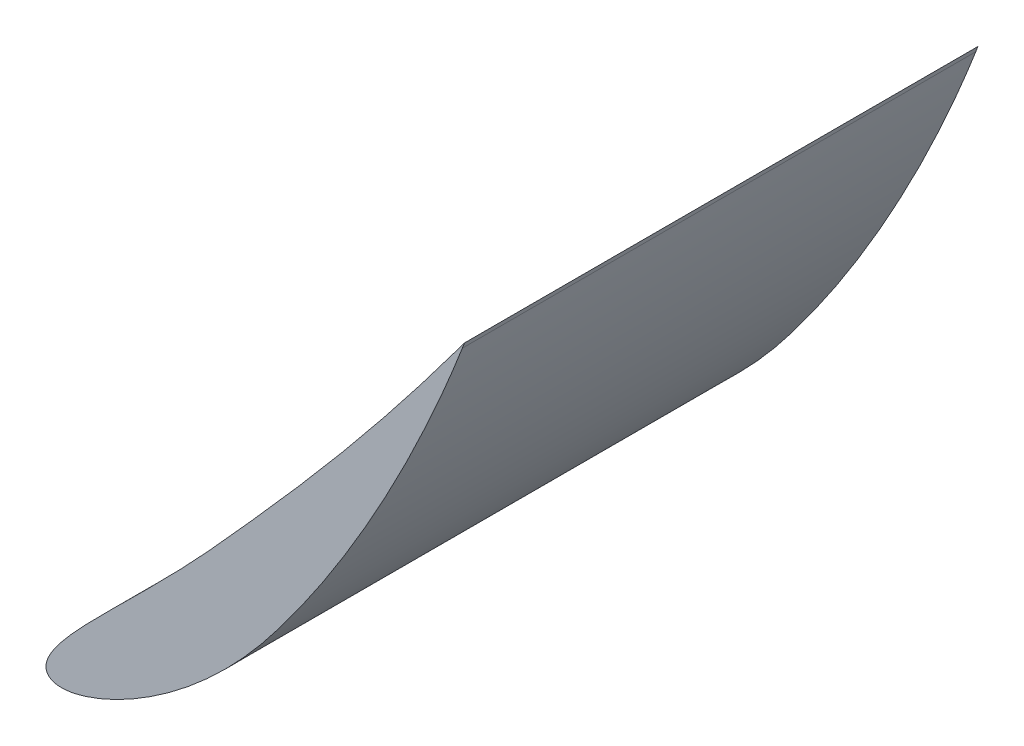
SolidWorks part; units mm, degrees
ref_plane "Front Plane" through (0, 0, 0) normal (0, 0, 1) x (1, 0, 0)
ref_plane "Top Plane" through (0, 0, 0) normal (0, 1, 0) x (1, 0, 0)
ref_plane "Right Plane" through (0, 0, 0) normal (1, 0, 0) x (0, 0, -1)
sketch "Sketch1" plane through (0, 0, 0) normal (0, 0, 1) x (1, 0, 0)
  line L12 (81.634, 97.2876) -> (0, 0) construction
  line L13 (81.5114, 97.3905) -> (81.7566, 97.1848) construction
  line L15 (0, 0) -> (49.9996, 0) construction
  line L16 (81.5114, 97.3905) -> (82.1927, 98.3086)
  line L17 (81.7566, 97.1848) -> (82.1927, 98.3086)
  spline S1 degree 3 poles (81.7566, 97.1848) (81.7317, 97.1205) (81.6321, 96.864) (81.4077, 96.2892) (81.0334, 95.3367) (80.5075, 94.0156) (79.829, 92.3376) (78.9965, 90.3178) (78.0086, 87.974) (76.8643, 85.3265) (75.5632, 82.3981) (74.105, 79.2134) (72.4912, 75.7986) (70.7234, 72.1816) (68.8046, 68.3914) (66.7394, 64.4574) (64.5329, 60.4101) (62.192, 56.2804) (59.7244, 52.0991) (57.1391, 47.8973) (54.4471, 43.705) (51.6593, 39.5528) (48.7894, 35.4693) (45.8491, 31.4847) (42.8637, 27.6176) (39.7792, 23.949) (36.6227, 20.4984) (33.4183, 17.2831) (30.1932, 14.317) (26.9767, 11.6105) (23.7993, 9.1714) (20.6932, 7.004) (17.6904, 5.1108) (14.8237, 3.491) (12.1246, 2.1423) (9.6232, 1.0613) (7.3474, 0.2422) (5.3215, -0.3201) (3.5651, -0.6329) (2.09, -0.7009) (0.8965, -0.5251) (-0.0134, -0.0818) (-0.579, 0.6607) (-0.6886, 1.6321) (-0.4133, 2.7429) (0.1968, 4.0285) (1.138, 5.5031) (2.4006, 7.1704) (3.9718, 9.0291) (5.834, 11.0763) (7.9665, 13.3081) (10.3447, 15.7209) (12.9427, 18.3096) (15.7314, 21.0695) (18.6806, 23.9946) (21.7585, 27.0784) (24.933, 30.313) (28.1717, 33.6891) (31.4437, 37.1956) (34.7151, 40.8229) (38.0269, 44.4942) (41.3443, 48.201) (44.6452, 51.9215) (47.9049, 55.6368) (51.1016, 59.325) (54.2144, 62.9647) (57.224, 66.5334) (60.1133, 70.0079) (62.8659, 73.3655) (65.468, 76.5829) (67.9066, 79.6376) (70.1703, 82.5079) (72.2485, 85.1731) (74.1325, 87.6134) (75.814, 89.8111) (77.286, 91.7497) (78.542, 93.415) (79.577, 94.7947) (80.3867, 95.8784) (80.9673, 96.6583) (81.3169, 97.1284) (81.4725, 97.338) (81.5114, 97.3905) knots 0 0 0 0 0.000791 0.00316 0.007087 0.012544 0.019489 0.027873 0.037633 0.048699 0.060994 0.074433 0.088923 0.104368 0.120665 0.13771 0.155392 0.173601 0.192223 0.211146 0.230254 0.249435 0.268577 0.287568 0.306301 0.324671 0.342595 0.359992 0.376786 0.392898 0.408252 0.422771 0.43638 0.449003 0.46057 0.471014 0.48028 0.488325 0.495133 0.500728 0.505217 0.508863 0.51207 0.515471 0.519696 0.525078 0.53175 0.539754 0.54908 0.559692 0.571531 0.584528 0.598598 0.61365 0.629586 0.6463 0.663686 0.681632 0.700027 0.718761 0.737727 0.756809 0.775888 0.794846 0.813569 0.83194 0.849847 0.86718 0.883834 0.899707 0.914701 0.928723 0.941687 0.953513 0.964128 0.973465 0.981467 0.988083 0.993272 0.997002 0.999249 1 1 1 1
  point P10 (81.634, 97.2876)
  dimension "D1" = 50
  dimension "D2" = 127
extrude "Boss-Extrude1" add sketch "Sketch1" along normal blind 101.6
sketch "Sketch2" plane through (0, 0, 101.6) normal (0, 0, 1) x (1, 0, 0)
  line L0 (81.5114, 97.3905) -> (81.7566, 97.1848) construction
  line L1 (81.634, 97.2876) -> (0, 0) construction
  line L2 (81.7566, 97.1848) -> (82.1927, 98.3086)
  line L3 (82.1927, 98.3086) -> (81.5114, 97.3905)
  line L4 (81.7566, 97.1848) -> (82.1927, 98.3086) construction
  line L5 (82.1927, 98.3086) -> (81.5114, 97.3905) construction
  line L6 (0, 0) -> (-10.9759, 9.2098) construction
  spline S1 degree 3 poles (2552.7951, -1600.9616) (120.8859, 159.412) (103.1981, 126.5505) (80.9673, 96.6583) (80.3867, 95.8784) (79.577, 94.7947) (78.542, 93.415) (77.286, 91.7497) (75.814, 89.8111) (74.1325, 87.6134) (72.2485, 85.1731) (70.1703, 82.5079) (67.9066, 79.6376) (65.468, 76.5829) (62.8659, 73.3655) (60.1133, 70.0079) (57.224, 66.5334) (54.2144, 62.9647) (51.1016, 59.325) (47.9049, 55.6368) (44.6452, 51.9215) (41.3443, 48.201) (38.0269, 44.4942) (34.7151, 40.8229) (31.4437, 37.1956) (28.1717, 33.6891) (24.933, 30.313) (21.7585, 27.0784) (18.6806, 23.9946) (15.7314, 21.0695) (12.9427, 18.3096) (10.3447, 15.7209) (7.9665, 13.3081) (5.834, 11.0763) (3.9718, 9.0291) (2.4006, 7.1704) (1.138, 5.5031) (0.1968, 4.0285) (-0.4133, 2.7429) (-0.6886, 1.6321) (-0.579, 0.6607) (-0.0134, -0.0818) (0.8965, -0.5251) (2.09, -0.7009) (3.5651, -0.6329) (5.3215, -0.3201) (7.3474, 0.2422) (9.6232, 1.0613) (12.1246, 2.1423) (14.8237, 3.491) (17.6904, 5.1108) (20.6932, 7.004) (23.7993, 9.1714) (26.9767, 11.6105) (30.1932, 14.317) (33.4183, 17.2831) (36.6227, 20.4984) (39.7792, 23.949) (42.8637, 27.6176) (45.8491, 31.4847) (48.7894, 35.4693) (51.6593, 39.5528) (54.4471, 43.705) (57.1391, 47.8973) (59.7244, 52.0991) (62.192, 56.2804) (64.5329, 60.4101) (66.7394, 64.4574) (68.8046, 68.3914) (70.7234, 72.1816) (72.4912, 75.7986) (74.105, 79.2134) (75.5632, 82.3981) (76.8643, 85.3265) (78.0086, 87.974) (78.9965, 90.3178) (79.829, 92.3376) (80.5075, 94.0156) (81.0334, 95.3367) (81.4077, 96.2892) (92.7855, 125.4365) (97.6499, 156.7488) (2908.7392, -903.0108) knots -0.421086 -0.421086 -0.421086 -0.421086 0.000751 0.002998 0.006728 0.011917 0.018533 0.026535 0.035872 0.046487 0.058313 0.071277 0.085299 0.100293 0.116166 0.13282 0.150153 0.16806 0.186431 0.205154 0.224112 0.243191 0.262273 0.281239 0.299973 0.318368 0.336314 0.3537 0.370414 0.38635 0.401402 0.415472 0.428469 0.440308 0.45092 0.460246 0.46825 0.474922 0.480304 0.484529 0.48793 0.491137 0.494783 0.499272 0.504867 0.511675 0.51972 0.528986 0.53943 0.550997 0.56362 0.577229 0.591748 0.607102 0.623214 0.640008 0.657405 0.675329 0.693699 0.712432 0.731423 0.750565 0.769746 0.788854 0.807777 0.826399 0.844608 0.86229 0.879335 0.895632 0.911077 0.925567 0.939006 0.951301 0.962367 0.972127 0.980511 0.987456 0.992913 0.99684 0.999209 1.352244 1.352244 1.352244 1.352244 only from (81.5114, 97.3905) to (81.7566, 97.1848)
  spline S2 degree 3 poles (81.5114, 97.3905) (81.4725, 97.338) (81.3169, 97.1284) (80.9673, 96.6583) (80.3867, 95.8784) (79.577, 94.7947) (78.542, 93.415) (77.286, 91.7497) (75.814, 89.8111) (74.1325, 87.6134) (72.2485, 85.1731) (70.1703, 82.5079) (67.9066, 79.6376) (65.468, 76.5829) (62.8659, 73.3655) (60.1133, 70.0079) (57.224, 66.5334) (54.2144, 62.9647) (51.1016, 59.325) (47.9049, 55.6368) (44.6452, 51.9215) (41.3443, 48.201) (38.0269, 44.4942) (34.7151, 40.8229) (31.4437, 37.1956) (28.1717, 33.6891) (24.933, 30.313) (21.7585, 27.0784) (18.6806, 23.9946) (15.7314, 21.0695) (12.9427, 18.3096) (10.3447, 15.7209) (7.9665, 13.3081) (5.834, 11.0763) (3.9718, 9.0291) (2.4006, 7.1704) (1.138, 5.5031) (0.1968, 4.0285) (-0.4133, 2.7429) (-0.6886, 1.6321) (-0.579, 0.6607) (-0.0134, -0.0818) (0.8965, -0.5251) (2.09, -0.7009) (3.5651, -0.6329) (5.3215, -0.3201) (7.3474, 0.2422) (9.6232, 1.0613) (12.1246, 2.1423) (14.8237, 3.491) (17.6904, 5.1108) (20.6932, 7.004) (23.7993, 9.1714) (26.9767, 11.6105) (30.1932, 14.317) (33.4183, 17.2831) (36.6227, 20.4984) (39.7792, 23.949) (42.8637, 27.6176) (45.8491, 31.4847) (48.7894, 35.4693) (51.6593, 39.5528) (54.4471, 43.705) (57.1391, 47.8973) (59.7244, 52.0991) (62.192, 56.2804) (64.5329, 60.4101) (66.7394, 64.4574) (68.8046, 68.3914) (70.7234, 72.1816) (72.4912, 75.7986) (74.105, 79.2134) (75.5632, 82.3981) (76.8643, 85.3265) (78.0086, 87.974) (78.9965, 90.3178) (79.829, 92.3376) (80.5075, 94.0156) (81.0334, 95.3367) (81.4077, 96.2892) (81.6321, 96.864) (81.7317, 97.1205) (81.7566, 97.1848) knots 0 0 0 0 0.000751 0.002998 0.006728 0.011917 0.018533 0.026535 0.035872 0.046487 0.058313 0.071277 0.085299 0.100293 0.116166 0.13282 0.150153 0.16806 0.186431 0.205154 0.224112 0.243191 0.262273 0.281239 0.299973 0.318368 0.336314 0.3537 0.370414 0.38635 0.401402 0.415472 0.428469 0.440308 0.45092 0.460246 0.46825 0.474922 0.480304 0.484529 0.48793 0.491137 0.494783 0.499272 0.504867 0.511675 0.51972 0.528986 0.53943 0.550997 0.56362 0.577229 0.591748 0.607102 0.623214 0.640008 0.657405 0.675329 0.693699 0.712432 0.731423 0.750565 0.769746 0.788854 0.807777 0.826399 0.844608 0.86229 0.879335 0.895632 0.911077 0.925567 0.939006 0.951301 0.962367 0.972127 0.980511 0.987456 0.992913 0.99684 0.999209 1 1 1 1 construction
  dimension "D1" = 0
